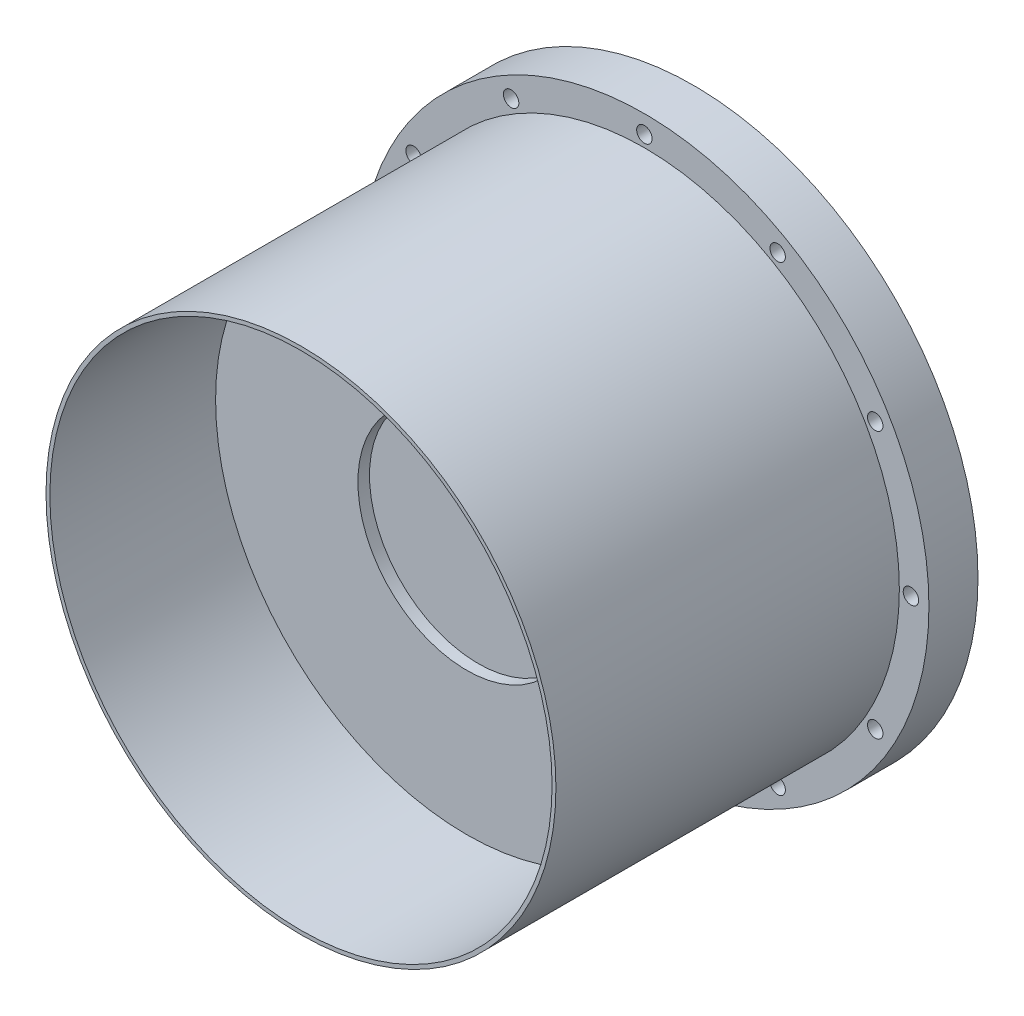
SolidWorks part; units mm, degrees
material "1060 Alloy"
ref_plane "Front Plane" through (0, 0, 0) normal (0, 0, 1) x (1, 0, 0)
ref_plane "Top Plane" through (0, 0, 0) normal (0, 1, 0) x (1, 0, 0)
ref_plane "Right Plane" through (0, 0, 0) normal (1, 0, 0) x (0, 0, -1)
sketch "Sketch1" plane through (0, 0, 0) normal (0, 0, 1) x (1, 0, 0)
  circle A0 centre (0, 0) radius 73.66
extrude "Boss-Extrude1" add sketch "Sketch1" along normal blind 12.7
sketch "Sketch2" plane through (0, 0, 12.7) normal (0, 0, 1) x (1, 0, 0)
  circle A0 centre (0, 69) radius 2
  circle A1 centre (34.5, 59.7558) radius 2
  circle A2 centre (59.7558, 34.5) radius 2
  circle A3 centre (69, 0) radius 2
  circle A4 centre (59.7558, -34.5) radius 2
  circle A5 centre (34.5, -59.7558) radius 2
  circle A6 centre (0, -69) radius 2
  circle A7 centre (-34.5, -59.7558) radius 2
  circle A8 centre (-59.7558, -34.5) radius 2
  circle A9 centre (-69, 0) radius 2
  circle A10 centre (-59.7558, 34.5) radius 2
  circle A11 centre (-34.5, 59.7558) radius 2
  dimension "D1" = 12
extrude "Cut-Extrude1" cut sketch "Sketch2" against normal blind 12.7
sketch "Sketch3" plane through (0, 0, 12.7) normal (0, 0, 1) x (1, 0, 0)
  circle A0 centre (0, 0) radius 66
  circle A1 centre (0, 0) radius 65
extrude "Boss-Extrude2" add sketch "Sketch3" along normal blind 88.9
ref_plane "Plane1" through (0, 0, 32.7) normal (0, 0, 1) x (1, 0, 0)
sketch "Sketch4" plane through (0, 0, 32.7) normal (0, 0, 1) x (1, 0, 0)
  circle A0 centre (0, 0) radius 65
  circle A1 centre (0, 0) radius 28.1626
extrude "Boss-Extrude3" add sketch "Sketch4" along normal blind 3
ref_plane "Plane2" through (0, 0, 55.7) normal (0, 0, 1) x (1, 0, 0)
sketch "Sketch5" plane through (0, 0, 55.7) normal (0, 0, 1) x (1, 0, 0)
  circle A0 centre (0, 0) radius 65
  circle A1 centre (0, 0) radius 28.1626
extrude "Boss-Extrude4" add sketch "Sketch5" along normal blind 3
sketch "Sketch6" plane through (0, 0, 12.7) normal (0, 0, 1) x (1, 0, 0)
  circle A0 centre (0, 0) radius 28.1626
extrude "Cut-Extrude2" cut sketch "Sketch6" against normal blind 300
